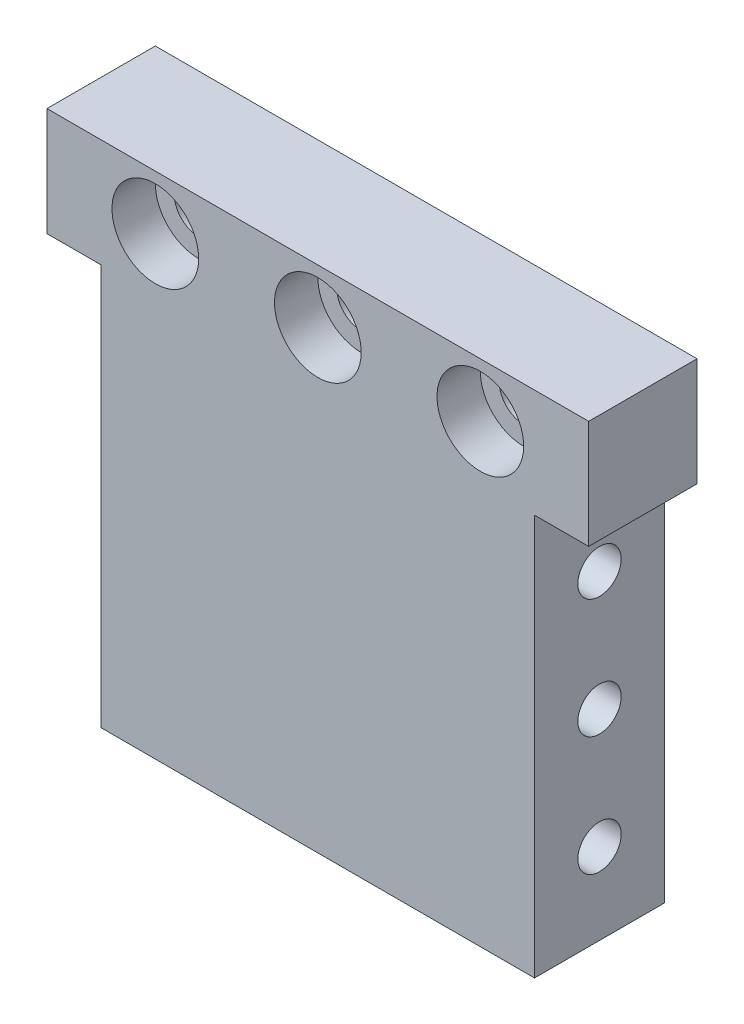
SolidWorks part; units mm, degrees
material "1060 합금"
ref_plane "정면" through (0, 0, 0) normal (0, 0, 1) x (1, 0, 0)
ref_plane "윗면" through (0, 0, 0) normal (0, 1, 0) x (1, 0, 0)
ref_plane "우측면" through (0, 0, 0) normal (1, 0, 0) x (0, 0, -1)
sketch "스케치1" plane through (0, 0, 0) normal (0, 0, 1) x (1, 0, 0)
  line L1 (0, 0) -> (50, 0)
  line L2 (0, 0) -> (0, 47)
  line L3 (0, 47) -> (50, 47)
  line L4 (50, 0) -> (50, 47)
  dimension "D1" = 50
  dimension "D2" = 47
extrude "보스-돌출1" add sketch "스케치1" along normal blind 12
sketch "스케치2" plane through (0, 0, 0) normal (0, 0, -1) x (-1, 0, 0)
  line L0 (-50, 0) -> (-50, 47) construction
  line L1 (0, 47) -> (-50, 47)
  line L2 (0, 47) -> (0, 37)
  line L3 (0, 37) -> (-50, 37)
  line L4 (-50, 47) -> (-50, 37)
  dimension "D1" = 10
extrude "컷-돌출1" cut sketch "스케치2" against normal blind 2
sketch "스케치4" plane through (0, 0, 12) normal (0, 0, 1) x (1, 0, 0)
  line L0 (50, 47) -> (0, 47) construction
  line L1 (0, 0) -> (5, 0)
  line L2 (0, 0) -> (0, 37)
  line L3 (0, 37) -> (5, 37)
  line L4 (5, 0) -> (5, 37)
  line L5 (50, 0) -> (45, 0)
  line L6 (50, 0) -> (50, 37)
  line L7 (50, 37) -> (45, 37)
  line L8 (45, 0) -> (45, 37)
  dimension "D1" = 10
  dimension "D2" = 10
  dimension "D3" = 5
  dimension "D4" = 5
sketch "스케치3" plane through (0, 0, 12) normal (0, 0, 1) x (1, 0, 0)
  line L0 (50, 42) -> (0, 42) construction
  line L1 (50, 47) -> (50, 37) construction
  line L2 (0, 47) -> (0, 0) construction
  circle A0 centre (25, 42) radius 2.25
  circle A1 centre (40, 42) radius 2.25
  circle A2 centre (10, 42) radius 2.25
  dimension "D1" = 4.5
  dimension "D2" = 4.5
  dimension "D3" = 4.5
  dimension "D4" = 15
  dimension "D5" = 15
extrude "컷-돌출2" cut sketch "스케치3" against normal through all
extrude "컷-돌출3" cut sketch "스케치4" against normal through all
sketch "스케치5" plane through (45, 0, 0) normal (1, 0, 0) x (0, 0, -1)
  line L0 (-6, 0) -> (-6, 37) construction
  line L1 (0, 0) -> (-12, 0) construction
  line L2 (-2, 37) -> (-12, 37) construction
  circle A0 centre (-6, 29.5) radius 2
  circle A1 centre (-6, 18.5) radius 2
  circle A2 centre (-6, 7.5) radius 2
  dimension "D1" = 4
  dimension "D2" = 4
  dimension "D3" = 4
  dimension "D4" = 7.5
  dimension "D5" = 11
  dimension "D6" = 11
extrude "컷-돌출4" cut sketch "스케치5" against normal blind 10
sketch "스케치6" plane through (5, 0, 0) normal (-1, 0, 0) x (0, 0, 1)
  line L0 (6, 0) -> (6, 37) construction
  line L1 (0, 0) -> (12, 0) construction
  line L2 (2, 37) -> (12, 37) construction
  circle A0 centre (6, 29.5) radius 2
  circle A1 centre (6, 18.5) radius 2
  circle A2 centre (6, 7.5) radius 2
  dimension "D1" = 4
  dimension "D2" = 4
  dimension "D3" = 4
  dimension "D4" = 7.5
  dimension "D5" = 11
  dimension "D6" = 11
extrude "컷-돌출5" cut sketch "스케치6" against normal blind 10
sketch "스케치7" plane through (0, 0, 12) normal (0, 0, 1) x (1, 0, 0)
  circle A0 centre (10, 42) radius 4
  circle A1 centre (25, 42) radius 4
  circle A2 centre (40, 42) radius 4
  dimension "D1" = 8
extrude "컷-돌출6" cut sketch "스케치7" against normal blind 4
